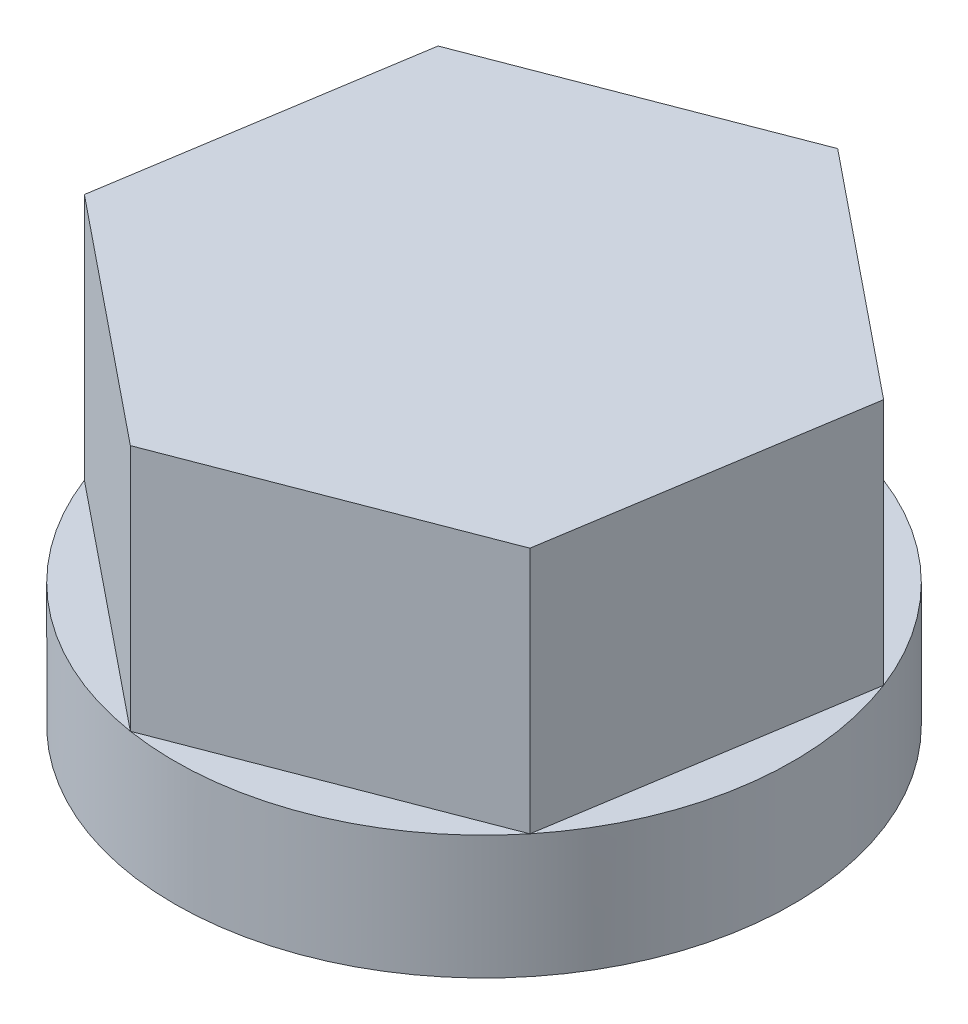
SolidWorks part; units mm, degrees
ref_plane "Спереди" through (0, 0, 0) normal (0, 0, 1) x (1, 0, 0)
ref_plane "Сверху" through (0, 0, 0) normal (0, 1, 0) x (1, 0, 0)
ref_plane "Справа" through (0, 0, 0) normal (1, 0, 0) x (0, 0, -1)
sketch "Эскиз1" plane through (0, 0, 0) normal (0, 1, 0) x (1, 0, 0)
  circle A0 centre (0, 0) radius 1.25
  point P3 (0, 0)
  dimension "D1" = 2.5
extrude "Бобышка-Вытянуть1" add sketch "Эскиз1" along normal blind 1.5 contours A0
sketch "Эскиз2" plane through (0, 0, 0) normal (0, -1, 0) x (1, 0, 0)
  circle A0 centre (0, 0) radius 0.95
  dimension "D1" = 1.9
extrude "Вырез-Вытянуть1" cut sketch "Эскиз2" against normal blind 1.2
sketch "Эскиз3" plane through (0, 1.5, 0) normal (0, 1, 0) x (1, 0, 0)
  line L1 (0.9718, -0.7861) -> (1.1667, 0.4486)
  line L2 (1.1667, 0.4486) -> (0.1949, 1.2347)
  line L3 (0.1949, 1.2347) -> (-0.9718, 0.7861)
  line L4 (-0.9718, 0.7861) -> (-1.1667, -0.4486)
  line L5 (-1.1667, -0.4486) -> (-0.1949, -1.2347)
  line L6 (-0.1949, -1.2347) -> (0.9718, -0.7861)
  circle A0 centre (0, 0) radius 1.0825 construction
  arc A1 (1.1667, 0.4486) -> (0.9718, -0.7861) centre (0, 0) cw
  arc A2 (1.1667, 0.4486) -> (0.1949, 1.2347) centre (0, 0) ccw
  arc A3 (-0.9718, 0.7861) -> (0.1949, 1.2347) centre (0, 0) ccw
  arc A4 (-1.1667, -0.4486) -> (-0.9718, 0.7861) centre (0, 0) cw
  arc A5 (-0.1949, -1.2347) -> (-1.1667, -0.4486) centre (0, 0) cw
  arc A6 (0.9718, -0.7861) -> (-0.1949, -1.2347) centre (0, 0) cw
  circle M8 centre (0, 0) radius 1.25
extrude "Вырез-Вытянуть2" cut sketch "Эскиз3" against normal blind 1 contours L6 M8 | L5 M8 | L4 M8 | L3 M8 | L2 M8 | L1 M8
